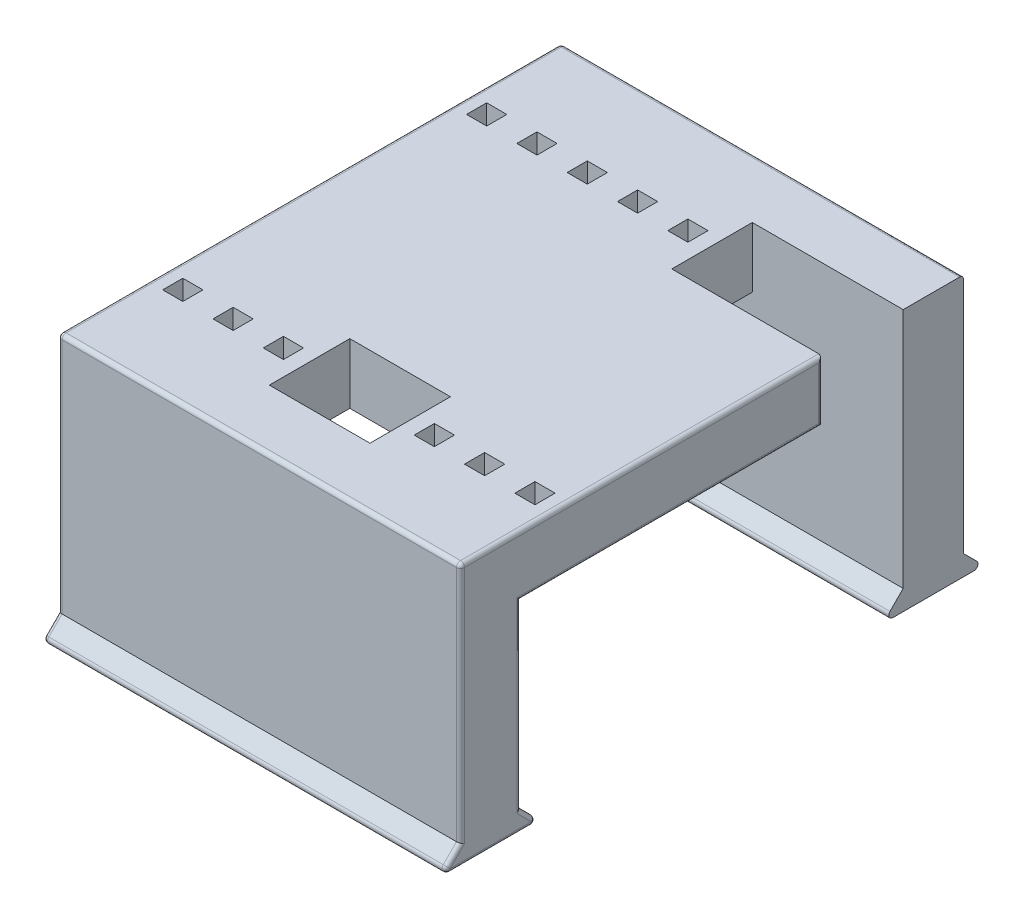
SolidWorks part; units mm, degrees
ref_plane "前视基准面" through (0, 0, 0) normal (0, 0, 1) x (1, 0, 0)
ref_plane "上视基准面" through (0, 0, 0) normal (0, 1, 0) x (1, 0, 0)
ref_plane "右视基准面" through (0, 0, 0) normal (1, 0, 0) x (0, 0, -1)
other "Configuration Table"
sketch "草图2" plane through (0, 0, 0) normal (0, 1, 0) x (1, 0, 0)
  line L0 (0, 0) -> (6.3014, 0) construction
  line L2 (0, 12.5) -> (20, 12.5)
  line L3 (0, 12.5) -> (0, -12.5)
  line L4 (0, -12.5) -> (20, -12.5)
  line L6 (0.75, -7.05) -> (1.75, -7.05)
  line L7 (0.75, -7.05) -> (0.75, -8.05)
  line L8 (0.75, -8.05) -> (1.75, -8.05)
  line L9 (1.75, -7.05) -> (1.75, -8.05)
  line L10 (20, 12.5) -> (20, -12.5)
  line L69 (3.25, -7.05) -> (4.25, -7.05)
  line L70 (3.25, -7.05) -> (3.25, -8.05)
  line L71 (3.25, -8.05) -> (4.25, -8.05)
  line L72 (4.25, -7.05) -> (4.25, -8.05)
  line L77 (5.75, -7.05) -> (6.75, -7.05)
  line L78 (5.75, -7.05) -> (5.75, -8.05)
  line L79 (5.75, -8.05) -> (6.75, -8.05)
  line L80 (6.75, -7.05) -> (6.75, -8.05)
  line L85 (8.25, -7.05) -> (9.25, -7.05)
  line L86 (8.25, -7.05) -> (8.25, -8.05)
  line L87 (8.25, -8.05) -> (9.25, -8.05)
  line L88 (9.25, -7.05) -> (9.25, -8.05)
  line L93 (10.75, -7.05) -> (11.75, -7.05)
  line L94 (10.75, -7.05) -> (10.75, -8.05)
  line L95 (10.75, -8.05) -> (11.75, -8.05)
  line L96 (11.75, -7.05) -> (11.75, -8.05)
  line L101 (13.25, -7.05) -> (14.25, -7.05)
  line L102 (13.25, -7.05) -> (13.25, -8.05)
  line L103 (13.25, -8.05) -> (14.25, -8.05)
  line L104 (14.25, -7.05) -> (14.25, -8.05)
  line L109 (15.75, -7.05) -> (16.75, -7.05)
  line L110 (15.75, -7.05) -> (15.75, -8.05)
  line L111 (15.75, -8.05) -> (16.75, -8.05)
  line L112 (16.75, -7.05) -> (16.75, -8.05)
  line L117 (18.25, -7.05) -> (19.25, -7.05)
  line L118 (18.25, -7.05) -> (18.25, -8.05)
  line L119 (18.25, -8.05) -> (19.25, -8.05)
  line L128 (19.25, -7.05) -> (19.25, -8.05)
  line L129 (19.25, 7.05) -> (19.25, 8.05)
  line L131 (18.25, 8.05) -> (19.25, 8.05)
  line L132 (18.25, 7.05) -> (18.25, 8.05)
  line L133 (18.25, 7.05) -> (19.25, 7.05)
  line L134 (16.75, 7.05) -> (16.75, 8.05)
  line L135 (15.75, 8.05) -> (16.75, 8.05)
  line L136 (15.75, 7.05) -> (15.75, 8.05)
  line L137 (15.75, 7.05) -> (16.75, 7.05)
  line L139 (14.25, 7.05) -> (14.25, 8.05)
  line L140 (13.25, 8.05) -> (14.25, 8.05)
  line L141 (13.25, 7.05) -> (13.25, 8.05)
  line L142 (13.25, 7.05) -> (14.25, 7.05)
  line L143 (11.75, 7.05) -> (11.75, 8.05)
  line L144 (10.75, 8.05) -> (11.75, 8.05)
  line L145 (10.75, 7.05) -> (10.75, 8.05)
  line L147 (10.75, 7.05) -> (11.75, 7.05)
  line L148 (9.25, 7.05) -> (9.25, 8.05)
  line L149 (8.25, 8.05) -> (9.25, 8.05)
  line L150 (8.25, 7.05) -> (8.25, 8.05)
  line L151 (8.25, 7.05) -> (9.25, 7.05)
  line L152 (6.75, 7.05) -> (6.75, 8.05)
  line L153 (5.75, 8.05) -> (6.75, 8.05)
  line L155 (5.75, 7.05) -> (5.75, 8.05)
  line L156 (5.75, 7.05) -> (6.75, 7.05)
  line L157 (4.25, 7.05) -> (4.25, 8.05)
  line L158 (3.25, 8.05) -> (4.25, 8.05)
  line L159 (3.25, 7.05) -> (3.25, 8.05)
  line L160 (3.25, 7.05) -> (4.25, 7.05)
  line L161 (1.75, 7.05) -> (1.75, 8.05)
  line L163 (0.75, 8.05) -> (1.75, 8.05)
  line L164 (0.75, 7.05) -> (0.75, 8.05)
  line L165 (0.75, 7.05) -> (1.75, 7.05)
  dimension "D1" = 7.05
  dimension "D2" = 25
  dimension "D3" = 1
  dimension "D4" = 20
  dimension "D5" = 0.75
  dimension "D6" = 8
extrude "凸台-拉伸1" add sketch "草图2" along normal blind 3
sketch "草图3" plane through (0, 0, 0) normal (0, -1, 0) x (1, 0, 0)
  line L0 (20, 12.5) -> (20, -12.5) construction
  line L1 (0, 12.5) -> (20, 12.5)
  line L2 (0, 12.5) -> (0, 9.5)
  line L3 (0, 9.5) -> (20, 9.5)
  line L4 (20, 12.5) -> (20, 9.5)
  line L5 (0, -12.5) -> (0, 12.5) construction
  line L6 (0, -9.5) -> (20, -9.5)
  line L7 (0, -9.5) -> (0, -12.5)
  line L8 (0, -12.5) -> (20, -12.5)
  line L9 (20, -9.5) -> (20, -12.5)
  dimension "D1" = 3
  dimension "D2" = 3
extrude "凸台-拉伸2" add sketch "草图3" along normal blind 10
sketch "草图5" plane through (0, 3, 0) normal (0, 1, 0) x (1, 0, 0)
  line L0 (12.5, 3.6346) -> (12.5, 0) construction
  line L1 (20, 5.5) -> (12.5, 5.5)
  line L2 (20, 5.5) -> (20, 9.5)
  line L3 (20, 9.5) -> (12.5, 9.5)
  line L4 (12.5, 5.5) -> (12.5, 9.5)
  line L5 (7.5, -5.5) -> (12.5, -5.5)
  line L6 (7.5, -5.5) -> (7.5, -9.5)
  line L7 (7.5, -9.5) -> (12.5, -9.5)
  line L8 (12.5, -5.5) -> (12.5, -9.5)
  line L11 (13.25, 8.05) -> (13.25, 7.05) construction
  line L12 (11.75, 7.05) -> (11.75, 8.05) construction
  line L13 (7.5, -3.0287) -> (7.5, -5.1489) construction
  line L14 (6.75, -8.05) -> (6.75, -7.05) construction
  line L15 (8.25, -7.05) -> (8.25, -8.05) construction
  line L16 (0, -9.5) -> (20, -9.5) construction
  dimension "D1" = 4
  dimension "D2" = 4
extrude "切除-拉伸1" cut sketch "草图5" against normal up to surface (3 mm away) up to face at (3.75, 0, -7.55)
sketch "草图4" plane through (20, 0, 0) normal (1, 0, 0) x (0, 0, -1)
  line L0 (-12.5, -10) -> (-13.5, -10)
  line L1 (-13.5, -10) -> (-12.5, -9)
  line L2 (-12.5, 3) -> (-12.5, -10) construction
  line L3 (-12.5, -9) -> (-12.5, -10)
  line L4 (9.5, -10) -> (8.5, -10)
  line L5 (8.5, -10) -> (9.5, -9)
  line L6 (9.5, -10) -> (9.5, 3) construction
  line L7 (9.5, -9) -> (9.5, -10)
  line L8 (12.5, -10) -> (13.5, -10)
  line L9 (13.5, -10) -> (12.5, -9)
  line L10 (12.5, 3) -> (12.5, -10) construction
  line L11 (12.5, -9) -> (12.5, -10)
  line L12 (-9.5, -10) -> (-8.5, -10)
  line L13 (-8.5, -10) -> (-9.5, -9)
  line L14 (-9.5, -10) -> (-9.5, 0) construction
  line L15 (-9.5, -9) -> (-9.5, -10)
  dimension "D1" = 1
  dimension "D2" = 1
  dimension "D3" = 1
  dimension "D4" = 1
extrude "凸台-拉伸3" add sketch "草图4" against normal up to surface (20 mm away) up to face at (0, -4.25, 0)
fillet "圆角1" radius 0.2 24 edges at (10, 3, -12.5) (20, 0, 2) (0, -10, 11) (0, 0, 0) (0, -10, -11) (20, 1.5, -5.5) (10, -10, 13.5) (20, -9.5, 13) (0, -9.5, 13) (0, -4.5, -9.5) (10, -10, -8.5) (0, -9.5, -9) (10, -10, -13.5) (0, -9.5, -13) (20, -4.5, 9.5) (0, -4.5, 9.5) (10, -10, 8.5) (20, -9.5, 9) (0, -9.5, 9) (0, 3, 0) (0, -3, -12.5) (20, -3, 12.5) (0, -3, 12.5) (10, 3, 12.5)
